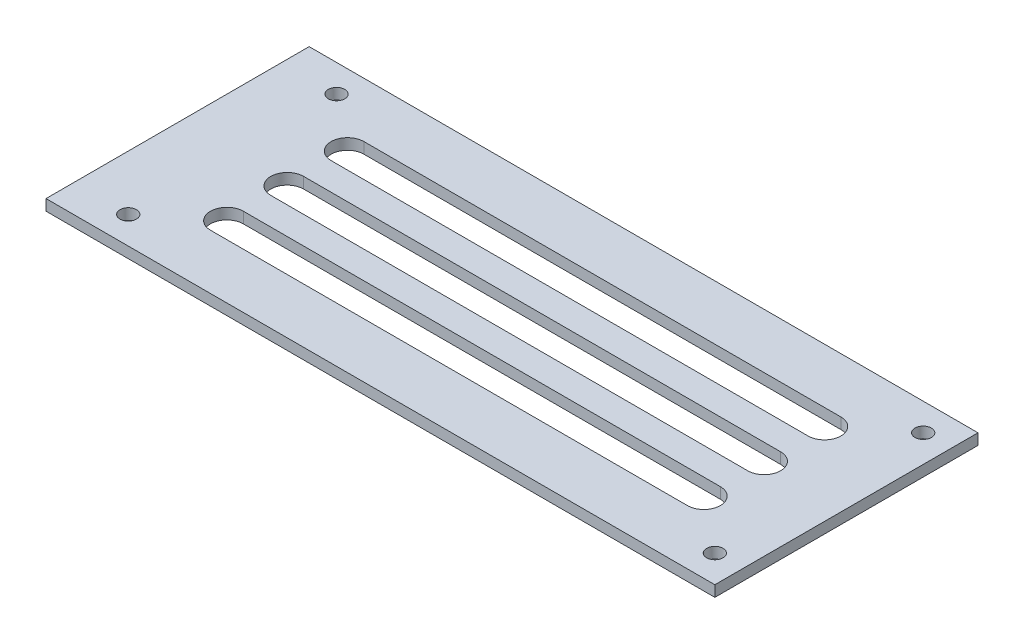
SolidWorks part; units mm, degrees
material "Thornel Mat VMA"
ref_plane "前视基准面" through (0, 0, 0) normal (0, 0, 1) x (1, 0, 0)
ref_plane "上视基准面" through (0, 0, 0) normal (0, 1, 0) x (1, 0, 0)
ref_plane "右视基准面" through (0, 0, 0) normal (1, 0, 0) x (0, 0, -1)
sketch "草图1" plane through (0, 0, 0) normal (0, 1, 0) x (1, 0, 0)
  line L1 (0, 0) -> (107, 0) construction
  line L2 (0, 0) -> (0, 38) construction
  line L3 (0, 38) -> (107, 38) construction
  line L4 (107, 0) -> (107, 38) construction
  line L5 (-10, -5) -> (112, -5)
  line L6 (-10, -5) -> (-10, 43)
  line L7 (-10, 43) -> (112, 43)
  line L8 (112, -5) -> (112, 43)
  circle A0 centre (0, 38) radius 1.5
  circle A1 centre (0, 0) radius 1.5
  circle A2 centre (107, 38) radius 1.5
  circle A3 centre (107, 0) radius 1.5
  dimension "D3" = 3
  dimension "D1" = 107
  dimension "D2" = 38
  dimension "D4" = 10
  dimension "D5" = 5
  dimension "D6" = 5
  dimension "D7" = 5
extrude "凸台-拉伸1" add sketch "草图1" along normal blind 2
sketch "草图2" plane through (0, 2, 0) normal (0, 1, 0) x (1, 0, 0)
  line L0 (10, 30) -> (97, 30) construction
  line L1 (10, 33) -> (97, 33)
  line L2 (10, 27) -> (97, 27)
  line L3 (112, 43) -> (-10, 43) construction
  line L4 (10, 16) -> (97, 16)
  line L5 (10, 22) -> (97, 22)
  line L6 (10, 19) -> (97, 19) construction
  line L7 (10, 5) -> (97, 5)
  line L8 (10, 11) -> (97, 11)
  line L9 (10, 8) -> (97, 8) construction
  line L10 (-10, -5) -> (112, -5) construction
  arc A0 (10, 33) -> (10, 27) centre (10, 30) ccw
  arc A1 (97, 27) -> (97, 33) centre (97, 30) ccw
  arc A2 (10, 22) -> (10, 16) centre (10, 19) ccw
  arc A3 (97, 16) -> (97, 22) centre (97, 19) ccw
  arc A4 (10, 11) -> (10, 5) centre (10, 8) ccw
  arc A5 (97, 5) -> (97, 11) centre (97, 8) ccw
  circle A6 centre (0, 38) radius 1.5 construction
  circle A7 centre (107, 38) radius 1.5 construction
  point P2 (53.5, 30)
  point P12 (53.5, 19)
  point P19 (53.5, 8)
  dimension "D4" = 3
  dimension "D1" = 10
  dimension "D3" = 10
  dimension "D5" = 10
  dimension "D6" = 10
  dimension "D2" = 3
extrude "切除-拉伸1" cut sketch "草图2" against normal through all
